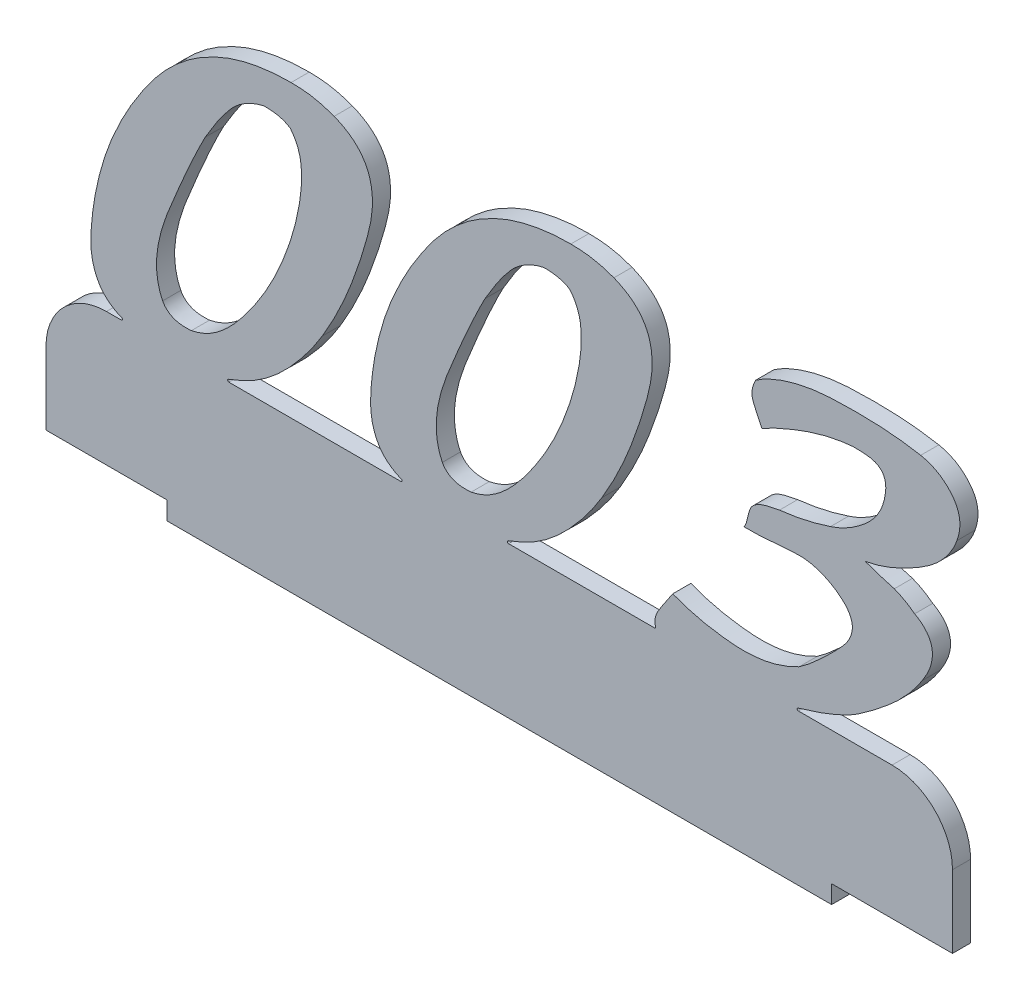
SolidWorks part; units mm, degrees
ref_plane "Front Plane" through (0, 0, 0) normal (0, 0, 1) x (1, 0, 0)
ref_plane "Top Plane" through (0, 0, 0) normal (0, 1, 0) x (1, 0, 0)
ref_plane "Right Plane" through (0, 0, 0) normal (1, 0, 0) x (0, 0, -1)
sketch "Sketch1" plane through (0, 0, 0) normal (0, 0, 1) x (1, 0, 0)
  line L0 (0, 20) -> (150, 20) construction
  line L1 (129.6705, 22) -> (150, 22)
  line L2 (0, 22) -> (0, 0)
  line L3 (0, 0) -> (20, 0)
  line L4 (150, 22) -> (150, 0)
  line L5 (0, 22) -> (13.7301, 22)
  line L6 (29.0517, 22) -> (60.0163, 22)
  line L7 (75.3379, 22) -> (100.9677, 22)
  line L8 (123.0423, 22) -> (129.6705, 22)
  line L11 (130, 0) -> (150, 0)
  line L13 (20, 0) -> (20, -3)
  line L14 (20, -3) -> (130, -3)
  line L15 (130, 0) -> (130, -3)
  spline S0 degree 3 poles (40.4172, 63.4795) (39.816, 63.889) (38.3507, 64.3951) (36.8129, 64.5224) (35.9997, 64.4763) knots 0 0 0 0 0.469699 1 1 1 1
  spline S1 degree 3 poles (35.9997, 64.4763) (34.855, 64.2357) (33.237, 63.5581) (31.3486, 62.1806) (29.0407, 59.6025) (27.507, 57.1509) (26.3633, 55.1722) knots 0 0 0 0 0.25259 0.375811 0.50377 1 1 1 1
  spline S2 degree 3 poles (26.3633, 55.1722) (25.907, 54.3741) (25.3088, 53.0576) (24.4173, 51.2385) (23.7038, 49.657) (22.9394, 47.9377) (22.1389, 46.071) (21.2823, 44.0748) (20.4103, 41.9865) (19.6173, 39.8883) (18.9856, 37.8609) (18.5448, 35.9539) (18.3019, 34.1608) (18.2546, 32.4815) (18.4563, 30.4558) (18.8758, 29.0322) (19.307, 28.1785) knots 0 0 0 0 0.095871 0.150957 0.21155 0.277044 0.347448 0.42366 0.503899 0.583776 0.657815 0.725493 0.787949 0.846481 0.90051 1 1 1 1
  spline S3 degree 3 poles (19.307, 28.1785) (19.6654, 27.4354) (21.1649, 26.2282) (23.0778, 26.2116) (24.0568, 26.2824) knots 0 0 0 0 0.446154 1 1 1 1
  spline S4 degree 3 poles (24.0568, 26.2824) (25.5143, 26.5568) (27.6709, 27.5752) (30.2032, 29.743) (32.1537, 31.9002) (34.0205, 34.3857) (35.782, 37.0597) (37.3724, 39.8862) (38.767, 42.8424) (39.9651, 45.8594) (40.9566, 48.8715) (41.6753, 51.86) (42.1799, 54.7506) (42.3495, 57.4523) (42.1476, 60.4829) (41.2728, 62.4714) (40.4172, 63.4795) knots 0 0 0 0 0.099523 0.157976 0.224341 0.295662 0.367825 0.440561 0.514606 0.588508 0.65979 0.72866 0.796042 0.857776 0.911265 1 1 1 1
  spline S5 degree 3 poles (13.7301, 22) (13.5754, 22.0445) (12.8983, 22.247) (11.7462, 22.6528) (10.4398, 23.5027) (9.3299, 24.5217) (8.5, 25.799) (7.8945, 27.2705) (7.3409, 29.6354) (7.4105, 31.5551) (7.5009, 32.8696) knots 0.483402 0.483402 0.483402 0.483402 0.501388 0.5623 0.61932 0.674488 0.729675 0.788153 0.851799 1 1 1 1
  spline S6 degree 3 poles (7.5009, 32.8696) (7.6678, 35.0977) (8.157, 38.4233) (9.2864, 42.7601) (10.3492, 45.9695) (11.7038, 49.1028) (13.2418, 52.2086) (15.0496, 55.2518) (17.0566, 58.2189) (19.2542, 61.0083) (21.7284, 63.4271) (24.3707, 65.5147) (27.2509, 67.1621) (30.2864, 68.5099) (34.7088, 69.7323) (38.1876, 70.117) (40.554, 70.0862) knots 0 0 0 0 0.122246 0.183381 0.245051 0.307032 0.370011 0.434579 0.500535 0.565958 0.62848 0.689454 0.749684 0.809559 0.870725 1 1 1 1
  spline S7 degree 3 poles (40.554, 70.0862) (41.8143, 70.0757) (44.2571, 69.9322) (46.5973, 69.2224) (47.6885, 68.8157) knots 0 0 0 0 0.519885 1 1 1 1
  spline S8 degree 3 poles (47.6885, 68.8157) (48.9561, 68.3004) (50.7511, 67.307) (52.4904, 65.3241) (53.4, 63.6506) (53.9152, 61.7457) (54.0805, 59.6287) (53.8874, 57.2979) (53.138, 53.9585) (51.8595, 49.7921) (49.5583, 43.4885) (47.3614, 39.0622) (45.6948, 36.3098) knots 0 0 0 0 0.111906 0.162582 0.212593 0.265416 0.321766 0.384451 0.454781 0.599581 0.738515 1 1 1 1
  spline S9 degree 3 poles (45.6948, 36.3098) (44.6033, 34.4526) (42.733, 31.8821) (39.9836, 28.7591) (37.8149, 26.6899) (35.4325, 24.8822) (32.7528, 23.3864) (30.5775, 22.5021) (29.3099, 22.0819) (29.0517, 22) knots 0 0 0 0 0.25786 0.380114 0.498337 0.616577 0.737567 0.865048 0.89749 0.89749 0.89749 0.89749
  spline S10 degree 3 poles (86.7034, 63.4795) (86.1021, 63.889) (84.6368, 64.3951) (83.099, 64.5224) (82.2859, 64.4763) knots 0 0 0 0 0.469699 1 1 1 1
  spline S11 degree 3 poles (82.2859, 64.4763) (81.1412, 64.2357) (79.5231, 63.5581) (77.6347, 62.1806) (75.3268, 59.6025) (73.7931, 57.1509) (72.6494, 55.1722) knots 0 0 0 0 0.25259 0.375811 0.50377 1 1 1 1
  spline S12 degree 3 poles (72.6494, 55.1722) (72.1931, 54.3741) (71.5949, 53.0576) (70.7034, 51.2385) (69.9899, 49.657) (69.2256, 47.9377) (68.4251, 46.071) (67.5685, 44.0748) (66.6964, 41.9865) (65.9034, 39.8883) (65.2718, 37.8609) (64.831, 35.9539) (64.5881, 34.1608) (64.5407, 32.4815) (64.7425, 30.4558) (65.162, 29.0322) (65.5931, 28.1785) knots 0 0 0 0 0.095871 0.150957 0.21155 0.277044 0.347448 0.42366 0.503899 0.583776 0.657815 0.725493 0.787949 0.846481 0.90051 1 1 1 1
  spline S13 degree 3 poles (65.5931, 28.1785) (65.9516, 27.4354) (67.4511, 26.2282) (69.364, 26.2116) (70.3429, 26.2824) knots 0 0 0 0 0.446154 1 1 1 1
  spline S14 degree 3 poles (70.3429, 26.2824) (71.8005, 26.5568) (73.9571, 27.5752) (76.4894, 29.743) (78.4398, 31.9002) (80.3066, 34.3857) (82.0681, 37.0597) (83.6586, 39.8862) (85.0531, 42.8424) (86.2513, 45.8594) (87.2428, 48.8715) (87.9615, 51.86) (88.466, 54.7506) (88.6356, 57.4523) (88.4338, 60.4829) (87.5589, 62.4714) (86.7034, 63.4795) knots 0 0 0 0 0.099523 0.157976 0.224341 0.295662 0.367825 0.440561 0.514606 0.588508 0.65979 0.72866 0.796042 0.857776 0.911265 1 1 1 1
  spline S15 degree 3 poles (60.0163, 22) (59.8615, 22.0445) (59.1844, 22.247) (58.0324, 22.6528) (56.726, 23.5027) (55.616, 24.5217) (54.7862, 25.799) (54.1807, 27.2705) (53.6271, 29.6354) (53.6967, 31.5551) (53.787, 32.8696) knots 0.483402 0.483402 0.483402 0.483402 0.501388 0.5623 0.61932 0.674488 0.729675 0.788153 0.851799 1 1 1 1
  spline S16 degree 3 poles (53.787, 32.8696) (53.954, 35.0977) (54.4431, 38.4233) (55.5725, 42.7601) (56.6354, 45.9695) (57.99, 49.1028) (59.528, 52.2086) (61.3357, 55.2518) (63.3428, 58.2189) (65.5403, 61.0083) (68.0146, 63.4271) (70.6569, 65.5147) (73.5371, 67.1621) (76.5726, 68.5099) (80.995, 69.7323) (84.4737, 70.117) (86.8402, 70.0862) knots 0 0 0 0 0.122246 0.183381 0.245051 0.307032 0.370011 0.434579 0.500535 0.565958 0.62848 0.689454 0.749684 0.809559 0.870725 1 1 1 1
  spline S17 degree 3 poles (86.8402, 70.0862) (88.1004, 70.0757) (90.5433, 69.9322) (92.8834, 69.2224) (93.9747, 68.8157) knots 0 0 0 0 0.519885 1 1 1 1
  spline S18 degree 3 poles (93.9747, 68.8157) (95.2422, 68.3004) (97.0373, 67.307) (98.7766, 65.3241) (99.6861, 63.6506) (100.2014, 61.7457) (100.3667, 59.6287) (100.1736, 57.2979) (99.4242, 53.9585) (98.1457, 49.7921) (95.8445, 43.4885) (93.6476, 39.0622) (91.9809, 36.3098) knots 0 0 0 0 0.111906 0.162582 0.212593 0.265416 0.321766 0.384451 0.454781 0.599581 0.738515 1 1 1 1
  spline S19 degree 3 poles (91.9809, 36.3098) (90.8894, 34.4526) (89.0192, 31.8821) (86.2698, 28.7591) (84.1011, 26.6899) (81.7187, 24.8822) (79.039, 23.3864) (76.8637, 22.5021) (75.5961, 22.0819) (75.3379, 22) knots 0 0 0 0 0.25786 0.380114 0.498337 0.616577 0.737567 0.865048 0.89749 0.89749 0.89749 0.89749
  spline S20 degree 3 poles (132.6572, 25.481) (130.4556, 24.3981) (127.2524, 23.1948) (123.972, 22.2495) (123.0423, 22) knots 0 0 0 0 0.226937 0.316065 0.316065 0.316065 0.316065
  spline S21 degree 3 poles (100.9677, 22) (100.9218, 22.1017) (100.788, 22.4786) (100.7313, 23.2124) (100.9645, 24.185) (101.9922, 25.9304) (103.0034, 27.2794) (103.7088, 28.3935) knots 0.07048 0.07048 0.07048 0.07048 0.113448 0.224396 0.348057 0.492967 1 1 1 1
  spline S22 degree 3 poles (103.7088, 28.3935) (105.365, 27.7532) (107.9296, 26.9733) (111.4701, 26.3922) (114.1778, 26.094) (116.9087, 26.1042) (120.4902, 26.5938) (123.0392, 27.5488) (124.6236, 28.3935) knots 0 0 0 0 0.247125 0.371259 0.498796 0.625702 0.750177 1 1 1 1
  spline S23 degree 3 poles (124.6236, 28.3935) (125.708, 29.1136) (127.3194, 30.5081) (129.5751, 32.6147) (131.1715, 34.2212) (132.3939, 35.6058) (133.0454, 36.6738) (133.3986, 37.7231) (133.4753, 38.7477) (133.2131, 39.7434) (132.4352, 41.0931) (131.46, 41.881) (130.7612, 42.3692) knots 0 0 0 0 0.209311 0.343078 0.497575 0.574369 0.640302 0.697767 0.75143 0.8034 0.861248 1 1 1 1
  spline S24 degree 3 poles (130.7612, 42.3692) (129.6615, 43.1264) (127.8444, 43.9913) (125.221, 44.4354) (121.3234, 44.2348) (118.1122, 43.8192) (115.5149, 43.8939) knots 0 0 0 0 0.255382 0.379223 0.505212 1 1 1 1
  spline S25 degree 3 poles (115.5149, 43.8939) (115.8177, 44.3286) (116.0815, 45.3705) (116.2963, 46.4134) (116.5118, 46.9236) knots 0 0 0 0 0.48539 1 1 1 1
  spline S26 degree 3 poles (116.5118, 46.9236) (116.7682, 47.6108) (118.3646, 48.7311) (120.234, 49.0194) (121.3789, 49.2301) knots 0 0 0 0 0.373078 1 1 1 1
  spline S27 degree 2 poles (121.3789, 49.2301) (125.7046, 49.6887) (129.823, 51.087) knots 0 0 0 1 1 1
  spline S28 degree 3 poles (129.823, 51.087) (130.8801, 51.4196) (132.431, 52.12) (134.3496, 53.3827) (135.7519, 54.4994) (137.0027, 55.7821) (138.3115, 57.7379) (138.8005, 59.4405) (138.9317, 60.5866) knots 0 0 0 0 0.23911 0.365172 0.495269 0.625648 0.750534 1 1 1 1
  spline S29 degree 3 poles (138.9317, 60.5866) (139.0173, 61.3865) (138.9211, 62.7343) (137.7011, 63.8696) (136.5183, 64.2633) (135.1576, 64.3945) (133.6568, 64.4578) (132.0369, 64.2675) (129.7257, 63.8823) (126.7647, 63.0965) (123.9037, 62.0342) (121.7725, 61.1104) (120.1393, 60.4017) (119.0873, 59.8223) (118.486, 59.4529) knots 0 0 0 0 0.105861 0.151148 0.202066 0.259997 0.323223 0.39085 0.464935 0.618432 0.775801 0.848984 0.911075 1 1 1 1
  spline S30 degree 3 poles (118.486, 59.4529) (118.0107, 60.4837) (117.3148, 61.7062) (116.7991, 63.319) (116.8222, 64.4892) (117.1373, 65.3314) (117.4305, 65.8641) knots 0 0 0 0 0.496027 0.61423 0.7339 1 1 1 1
  spline S31 degree 3 poles (117.4305, 65.8641) (119.2255, 67.0957) (122.3683, 68.3767) (126.9419, 69.3455) (130.7564, 69.6174) (134.5928, 69.6633) (139.2749, 69.5283) (142.6266, 69.1588) (144.737, 68.757) knots 0 0 0 0 0.231433 0.359702 0.498958 0.639815 0.770266 1 1 1 1
  spline S32 degree 3 poles (144.737, 68.757) (145.7764, 68.5447) (147.2916, 68.0011) (148.9783, 66.7278) (150.0515, 65.5958) (150.8556, 64.2646) (151.4181, 62.1956) (151.1159, 60.5533) (150.7378, 59.5311) knots 0 0 0 0 0.252438 0.373944 0.498635 0.620593 0.739093 1 1 1 1
  spline S33 degree 3 poles (150.7378, 59.5311) (150.2443, 58.1234) (148.9941, 56.1491) (146.6581, 53.9532) (144.4763, 52.5149) (142.17, 51.27) (139.2552, 49.9146) (137.0333, 49.2276) (135.5697, 48.9759) knots 0 0 0 0 0.231688 0.359129 0.498309 0.638598 0.768407 1 1 1 1
  spline S34 degree 3 poles (135.5697, 48.9759) (136.4461, 48.7125) (138.0141, 48.0966) (139.6412, 47.6629) (140.3781, 47.4513) knots 0 0 0 0 0.54394 1 1 1 1
  spline S35 degree 2 poles (140.3781, 47.4513) (142.2043, 46.7462) (143.7401, 45.5358) knots 0 0 0 1 1 1
  spline S36 degree 3 poles (143.7401, 45.5358) (144.5154, 45.1349) (145.5115, 44.3416) (146.3926, 42.9628) (146.6814, 41.8529) (146.6916, 40.6562) (146.3096, 38.8164) (145.5661, 37.5032) (145.0106, 36.6225) knots 0 0 0 0 0.250144 0.357669 0.464359 0.574792 0.698847 1 1 1 1
  spline S37 degree 3 poles (145.0106, 36.6225) (144.191, 35.3233) (142.7318, 33.477) (140.4707, 31.2141) (138.5862, 29.6241) (136.7621, 28.1893) (134.8179, 26.7848) (133.4848, 25.9047) (132.6572, 25.481) knots 0 0 0 0 0.274285 0.419249 0.571241 0.71478 0.834078 1 1 1 1
  dimension "D1" = 150
  dimension "D2" = 3
  dimension "D3" = 20
  dimension "D4" = 20
  dimension "D5" = 20
extrude "Boss-Extrude1" add sketch "Sketch1" along normal blind 3
fillet "Fillet1" radius 10 2 edges at (0, 22, 1.5) (150, 22, 1.5)
fillet "Fillet2" radius 0.2 6 edges at (13.7301, 22, 1.5) (60.0163, 22, 1.5) (100.9677, 22, 1.5) (123.0423, 22, 1.5) (75.3379, 22, 1.5) (29.0517, 22, 1.5)
